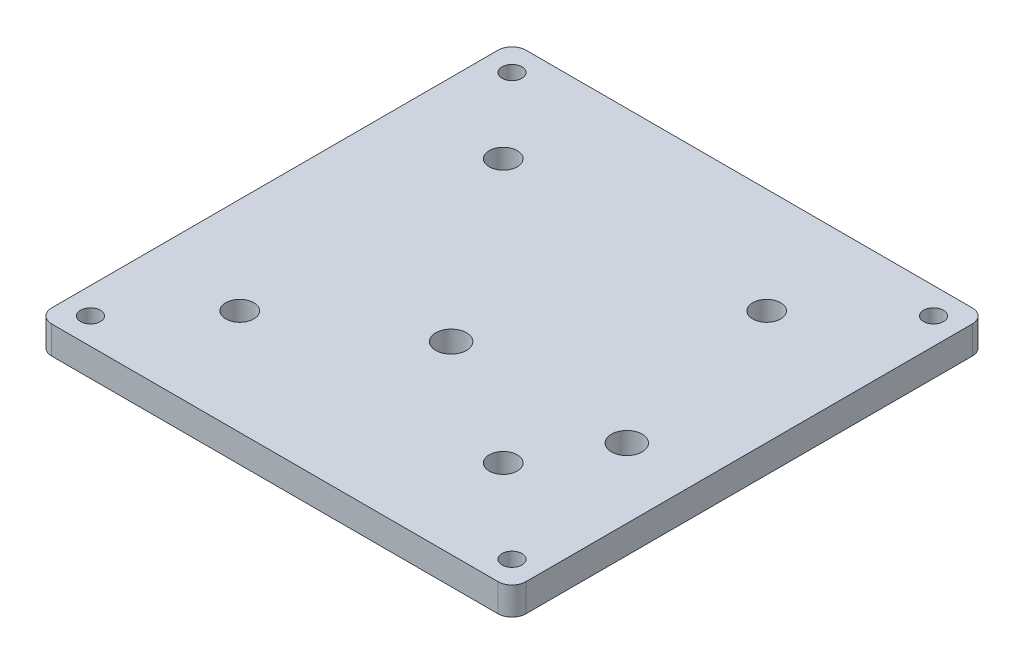
SolidWorks part; units mm, degrees
material "AISI 4130 Steel, annealed at 865C"
ref_plane "Front Plane" through (0, 0, 0) normal (0, 0, 1) x (1, 0, 0)
ref_plane "Top Plane" through (0, 0, 0) normal (0, 1, 0) x (1, 0, 0)
ref_plane "Right Plane" through (0, 0, 0) normal (1, 0, 0) x (0, 0, -1)
sketch "Sketch1" plane through (0, 0, 0) normal (0, 1, 0) x (1, 0, 0)
  line L0 (5, -7) -> (5, -37) construction
  line L1 (0, 0) -> (42, 0)
  line L2 (0, 0) -> (0, -44)
  line L3 (0, -44) -> (42, -44)
  line L4 (42, 0) -> (42, -44)
  line L5 (35, -7) -> (5, -7) construction
  line L6 (38, 2.5) -> (38, 0) construction
  line L7 (21, 0) -> (21, -44) construction
  line L8 (42, 0) -> (49.18, 0)
  line L9 (49.18, 0) -> (49.18, -44)
  line L10 (49.18, -44) -> (42, -44)
  line L11 (21, -22) -> (-15.2405, -22) construction
  line L12 (20.07, -28) -> (40.07, -28) construction
  line L13 (38, -46.5) -> (38, -44) construction
  line L15 (0, -44) -> (42, -44)
  line L16 (0, -44) -> (0, -49)
  line L17 (0, -49) -> (42, -49)
  line L18 (42, -44) -> (42, -49)
  line L19 (0, 0) -> (42, 0)
  line L20 (0, 0) -> (0, 5)
  line L21 (0, 5) -> (42, 5)
  line L22 (42, 0) -> (42, 5)
  circle A0 centre (5, -7) radius 1.6
  circle A1 centre (35, -7) radius 1.6
  circle A2 centre (35, -37) radius 1.6
  circle A3 centre (5, -37) radius 1.6
  circle A8 centre (20.07, -28) radius 1.75
  circle A9 centre (40.07, -28) radius 1.75
  circle A10 centre (38, 2.5) radius 0.5 construction
  circle A11 centre (38, -46.5) radius 0.5 construction
  circle A12 centre (4, 2.5) radius 0.5 construction
  circle A13 centre (4, -46.5) radius 0.5 construction
  dimension "D1" = 3.2
  dimension "D13" = 3.5
  dimension "D10" = 1
  dimension "D3" = 30
  dimension "D4" = 30
  dimension "D6" = 42
  dimension "D7" = 44
  dimension "D8" = 7
  dimension "D9" = 7
  dimension "D11" = 7.18
  dimension "D14" = 20
  dimension "D5" = 0.93
  dimension "D2" = 6
  dimension "D15" = 4
  dimension "D16" = 5
  dimension "D17" = 4
  dimension "D12" = 2.5
extrude "Boss-Extrude1" add sketch "Sketch1" along normal blind 3.175 contours L1 L22 L21 L20 A12 A10 | L4 L1 L2 L3 A9 A8 A3 A2 A1 A0 | L18 L3 L16 L17 A13 A11
sketch "Sketch2" plane through (0, 3.175, 0) normal (0, 1, 0) x (1, 0, 0)
  line L1 (0, 5) -> (-6, 5)
  line L2 (0, 5) -> (0, -49)
  line L3 (0, -49) -> (-6, -49)
  line L4 (-6, 5) -> (-6, -49)
  line L5 (42, 5) -> (48, 5)
  line L6 (42, 5) -> (42, -49)
  line L7 (42, -49) -> (48, -49)
  line L8 (48, 5) -> (48, -49)
  circle A0 centre (45, 2) radius 2.3241 construction
  circle A1 centre (-3, 2) radius 2.3241 construction
  circle A2 centre (-3, -46) radius 2.3241 construction
  circle A3 centre (45, -46) radius 2.3241 construction
  point P10 (45, 2)
  point P12 (45, -46)
  point P14 (-3, 2)
  point P15 (-3, -46)
  line M18 (0, 5) -> (0, -49)
  line M26 (42, -49) -> (42, 5)
  dimension "D6" = 4.6482
  dimension "D1" = 6
  dimension "D2" = 3
  dimension "D3" = 3
  dimension "D4" = 3
  dimension "D5" = 3
extrude "Boss-Extrude2" add sketch "Sketch2" against normal up to surface (3.175 mm away) contours L1 L4 L3 M18 | L8 L5 L7 M26 up to face at (21, 0, 22)
hole_wizard "#4-40 Tapped Hole1" positions "3DSketch1" profile "Sketch3" tap size "#4-40" standard "ANSI Inch" end condition through all
sketch3d "3DSketch1"
  point P3 (-3, 3.175, -2)
  point P6 (-3, 3.175, 46)
  point P9 (45, 3.175, -2)
  point P12 (45, 3.175, 46)
sketch "Sketch3" plane through (-3, 3.175, -2) normal (1, 0, 0) x (0, 0, 1)
  line L0 (0, 0) -> (0, 3.175)
  line L1 (0, 3.175) -> (1.1303, 3.175)
  line L2 (1.1303, 3.175) -> (1.1303, 0)
  line L5 (1.1303, 0) -> (0, 0)
  line L11 (0, -6.35) -> (0, 107.95) construction
  dimension "Thru Tap Drill Dia." = 2.2606
  dimension "Thru Tap Drill Depth" = 3.175
cosmetic thread "Hole Thread1" parameters "D2"=2.8448
cosmetic thread "Hole Thread2" parameters "D2"=2.8448
cosmetic thread "Hole Thread3" parameters "D2"=2.8448
cosmetic thread "Hole Thread4" parameters "D2"=2.8448
fillet "Fillet1" radius 1.5875 4 edges at (-6, 1.5875, -5) (48, 1.5875, -5) (48, 1.5875, 49) (-6, 1.5875, 49)
equation "\"D8@Sketch1\"=(\"D7@Sketch1\"-\"D4@Sketch1\")/2"
equation "\"D9@Sketch1\"=\"D8@Sketch1\""
equation "\"D3@Sketch2\"=\"D2@Sketch2\""
equation "\"D4@Sketch2\"=\"D2@Sketch2\""
equation "\"D5@Sketch2\"=\"D2@Sketch2\""
equation "\"D5@Sketch1\"=9.37mm-6.3-2-0.14"
equation "\"D17@Sketch1\"=\"D15@Sketch1\""
equation "\"D12@Sketch1\"=\"D16@Sketch1\"/2"
